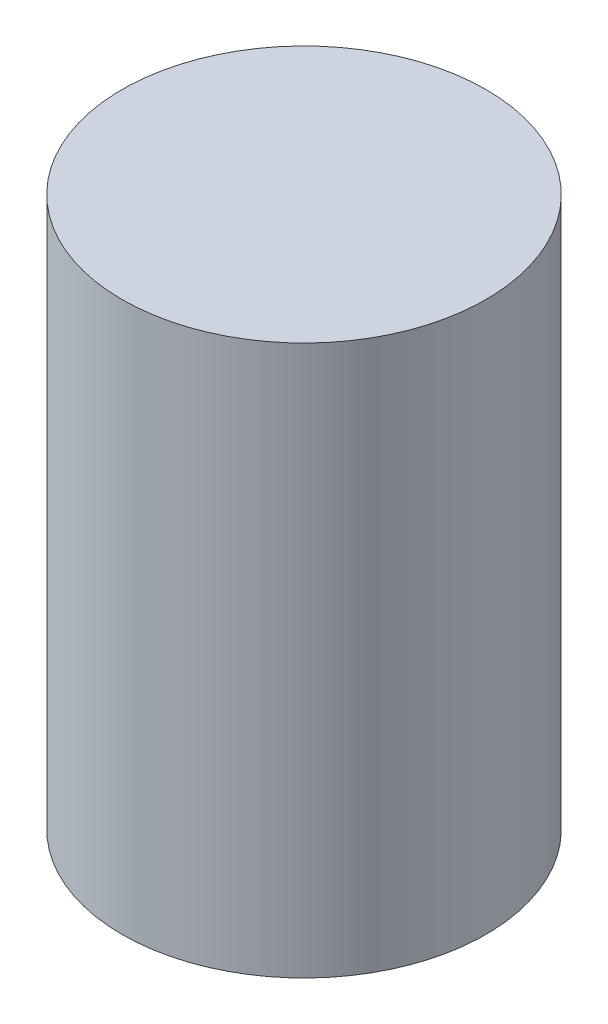
SolidWorks part; units mm, degrees
ref_plane "Front Plane" through (0, 0, 0) normal (0, 0, 1) x (1, 0, 0)
ref_plane "Top Plane" through (0, 0, 0) normal (0, 1, 0) x (1, 0, 0)
ref_plane "Right Plane" through (0, 0, 0) normal (1, 0, 0) x (0, 0, -1)
sketch "CurveSketch" plane through (0, 0, 0) normal (0, 1, 0) x (1, 0, 0)
  circle A0 centre (-7.137, 2.617) radius 9.137
  dimension "D1" = 18.274
extrude "CurveBoss" add sketch "CurveSketch" against normal blind 27.617
